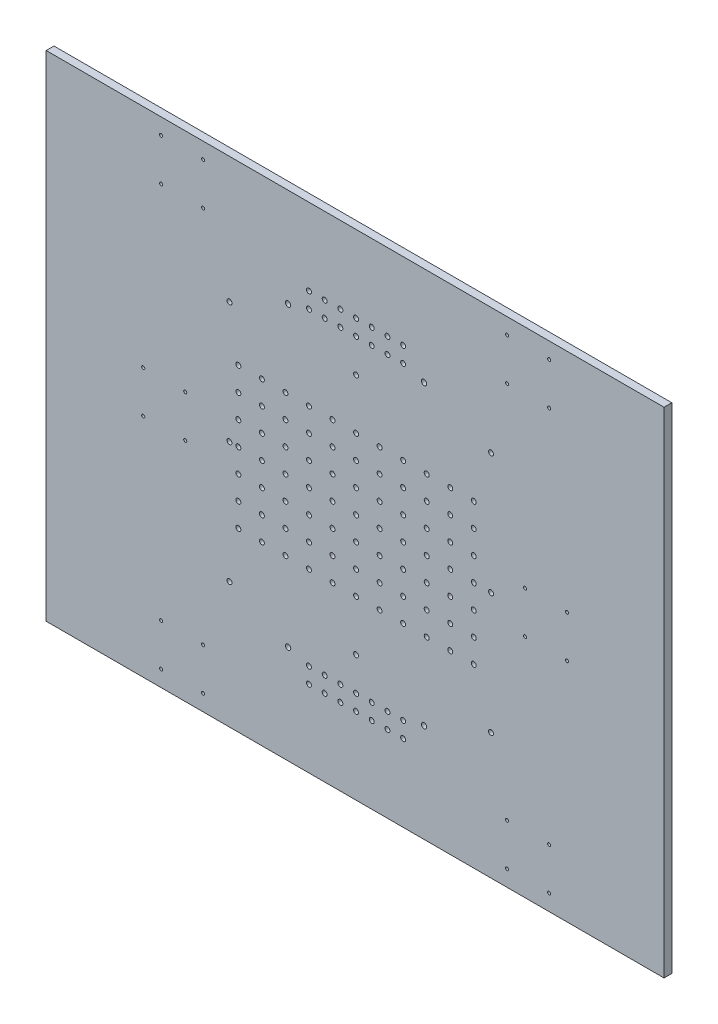
SolidWorks part; units mm, degrees
ref_plane "Front Plane" through (0, 0, 0) normal (0, 0, 1) x (1, 0, 0)
ref_plane "Top Plane" through (0, 0, 0) normal (0, 1, 0) x (1, 0, 0)
ref_plane "Right Plane" through (0, 0, 0) normal (1, 0, 0) x (0, 0, -1)
sketch "Sketch1" plane through (0, 0, 0) normal (0, 0, 1) x (1, 0, 0)
  line L1 (-250, 200) -> (250, 200)
  line L2 (-250, 200) -> (-250, -200)
  line L3 (-250, -200) -> (250, -200)
  line L4 (250, 200) -> (250, -200)
  dimension "D1" = 500
  dimension "D2" = 400
  dimension "D3" = 200
  dimension "D4" = 250
extrude "Base_Plate-Extrude" add sketch "Sketch1" along normal blind 6.3
sketch "Sketch2" plane through (0, 0, 6.3) normal (0, 0, 1) x (1, 0, 0)
  line L0 (140, 239.4193) -> (140, -239.7265) construction
  line L1 (274.5626, 0) -> (-272.804, 0) construction
  line L2 (250, -200) -> (250, 200) construction
  line L3 (274.5626, 170) -> (79.3115, 170) construction
  line L4 (274.5626, -170) -> (79.3115, -170) construction
  line L6 (-154.4486, 296.3867) -> (-154.4486, -298.16) construction
  line L8 (0, 280.9567) -> (0, -269.742) construction
  circle A0 centre (157, 153) radius 1.25
  circle A1 centre (157, 187) radius 1.25
  circle A2 centre (123, 187) radius 1.25
  circle A3 centre (123, 153) radius 1.25
  circle A7 centre (157, -153) radius 1.25
  circle A8 centre (157, -187) radius 1.25
  circle A9 centre (123, -153) radius 1.25
  circle A10 centre (123, -187) radius 1.25
  circle A11 centre (-137.4486, 17) radius 1.25
  circle A12 centre (-137.4486, -17) radius 1.25
  circle A13 centre (-171.4486, -17) radius 1.25
  circle A14 centre (-171.4486, 17) radius 1.25
  circle A15 centre (171.4486, -17) radius 1.25
  circle A16 centre (171.4486, 17) radius 1.25
  circle A17 centre (137.4486, 17) radius 1.25
  circle A18 centre (137.4486, -17) radius 1.25
  circle A19 centre (-157, -153) radius 1.25
  circle A20 centre (-123, -153) radius 1.25
  circle A21 centre (-123, -187) radius 1.25
  circle A22 centre (-157, -187) radius 1.25
  circle A23 centre (-157, 187) radius 1.25
  circle A24 centre (-123, 187) radius 1.25
  circle A25 centre (-123, 153) radius 1.25
  circle A26 centre (-157, 153) radius 1.25
  point P39 (140, -170)
  point P40 (140, 170)
  point P41 (-154.4486, 0)
  point P42 (0, 0)
  point P43 (0, 0)
  point P44 (0, 0)
  point P45 (0, 0)
  point P46 (0, 0)
  point P47 (0, 0)
  point P48 (0, 0)
  dimension "D4" = 2.5
  dimension "D7" = 2.5
  dimension "D8" = 2.5
  dimension "D9" = 2.5
  dimension "D16" = 2.5
  dimension "D17" = 2.5
  dimension "D18" = 2.5
  dimension "D19" = 2.5
  dimension "D29" = 2.5
  dimension "D30" = 2.5
  dimension "D31" = 2.5
  dimension "D32" = 2.5
  dimension "D1" = 110
  dimension "D2" = 170
  dimension "D3" = 170
  dimension "D5" = 17
  dimension "D6" = 17
  dimension "D10" = 17
  dimension "D11" = 17
  dimension "D12" = 17
  dimension "D13" = 17
  dimension "D14" = 17
  dimension "D15" = 17
  dimension "D20" = 17
  dimension "D21" = 17
  dimension "D22" = 17
  dimension "D23" = 17
  dimension "D24" = 17
  dimension "D25" = 17
  dimension "D26" = 17
  dimension "D27" = 17
  dimension "D33" = 17
  dimension "D34" = 17
  dimension "D35" = 17
  dimension "D36" = 17
  dimension "D37" = 17
  dimension "D38" = 17
  dimension "D39" = 17
  dimension "D40" = 17
  dimension "D28" = 340
extrude "Tripod_Adapater_Fasteners-Thru-Hole" cut sketch "Sketch2" against normal through all
sketch "Sketch3" plane through (0, 0, 6.3) normal (0, 0, 1) x (1, 0, 0)
  line L0 (218.6774, 98) -> (-212.5391, 98) construction
  line L1 (218.7113, -98) -> (-212.5283, -98) construction
  line L2 (110, 226.7998) -> (110, -231.3038) construction
  line L3 (250, -200) -> (250, 200) construction
  line L4 (-101.66, 174.4237) -> (-101.66, -178.7911) construction
  line L5 (282.3614, 0) -> (-354.7069, 0) construction
  line L6 (55.78, 225.6084) -> (55.78, -232.4952) construction
  line L7 (-54.22, -232.4952) -> (-54.22, 225.6084) construction
  line L8 (95.7553, 120.25) -> (-187.2723, 120.25) construction
  line L9 (88.1602, -120.25) -> (-163.8184, -120.25) construction
  circle A0 centre (110, 98) radius 2
  circle A1 centre (0.78, 98) radius 2
  circle A2 centre (-101.66, 98) radius 2
  circle A3 centre (-101.66, -98) radius 2
  circle A4 centre (0.78, -98) radius 2
  circle A5 centre (110, -98) radius 2
  circle A8 centre (110, 0) radius 2
  circle A9 centre (-101.66, 0) radius 2
  circle A85 centre (55.78, -120.25) radius 2.15
  circle A86 centre (-54.22, -120.25) radius 2.15
  circle A87 centre (-54.22, 120.25) radius 2.15
  circle A88 centre (55.78, 120.25) radius 2.15
  point P45 (0, 0)
  point P46 (0, 0)
  point P47 (0, 0)
  point P48 (0, 0)
  point P49 (0, 0)
  point P50 (0, 0)
  point P51 (0, 0)
  point P52 (0, 0)
  point P53 (0, 0)
  dimension "D1" = 4
  dimension "D8" = 4
  dimension "D9" = 4
  dimension "D10" = 4
  dimension "D11" = 4
  dimension "D12" = 4
  dimension "D16" = 4
  dimension "D17" = 4
  dimension "D20" = 4.3
  dimension "D21" = 4.3
  dimension "D22" = 4.3
  dimension "D23" = 4.3
  dimension "D3" = 109.22
  dimension "D4" = 102.44
  dimension "D5" = 102.44
  dimension "D6" = 109.22
  dimension "D2" = 196
  dimension "D7" = 98
  dimension "D13" = 140
  dimension "D14" = 98
  dimension "D15" = 98
  dimension "D18" = 110
  dimension "D19" = 240.5
  dimension "D24" = 120.25
  dimension "D25" = 55
extrude "Plate_to_Plate_Mnt-Thru-Hole" cut sketch "Sketch3" against normal through all
sketch "Sketch4" plane through (0, 0, 6.3) normal (0, 0, 1) x (1, 0, 0)
  line L0 (283.705, 0) -> (-313.8392, 0) construction
  circle A0 centre (-94.47, 0) radius 2
  circle A1 centre (-101.66, 0) radius 2 construction
  circle A2 centre (-75.42, 0) radius 2
  circle A3 centre (-56.37, 0) radius 2
  circle A4 centre (-37.32, 0) radius 2
  circle A5 centre (-18.27, 0) radius 2
  circle A6 centre (0.78, 0) radius 2
  circle A7 centre (19.83, 0) radius 2
  circle A8 centre (38.88, 0) radius 2
  circle A9 centre (57.93, 0) radius 2
  circle A10 centre (76.98, 0) radius 2
  circle A11 centre (96.03, 0) radius 2
  circle A12 centre (-94.47, 19.05) radius 2
  circle A13 centre (-75.42, 19.05) radius 2
  circle A14 centre (-56.37, 19.05) radius 2
  circle A15 centre (-37.32, 19.05) radius 2
  circle A16 centre (-18.27, 19.05) radius 2
  circle A17 centre (0.78, 19.05) radius 2
  circle A18 centre (19.83, 19.05) radius 2
  circle A19 centre (38.88, 19.05) radius 2
  circle A20 centre (57.93, 19.05) radius 2
  circle A21 centre (76.98, 19.05) radius 2
  circle A22 centre (96.03, 19.05) radius 2
  circle A23 centre (-94.47, 38.1) radius 2
  circle A24 centre (-75.42, 38.1) radius 2
  circle A25 centre (-56.37, 38.1) radius 2
  circle A26 centre (-37.32, 38.1) radius 2
  circle A27 centre (-18.27, 38.1) radius 2
  circle A28 centre (0.78, 38.1) radius 2
  circle A29 centre (19.83, 38.1) radius 2
  circle A30 centre (38.88, 38.1) radius 2
  circle A31 centre (57.93, 38.1) radius 2
  circle A32 centre (76.98, 38.1) radius 2
  circle A33 centre (96.03, 38.1) radius 2
  circle A34 centre (-94.47, 57.15) radius 2
  circle A35 centre (-75.42, 57.15) radius 2
  circle A36 centre (-56.37, 57.15) radius 2
  circle A37 centre (-37.32, 57.15) radius 2
  circle A38 centre (-18.27, 57.15) radius 2
  circle A39 centre (0.78, 57.15) radius 2
  circle A40 centre (19.83, 57.15) radius 2
  circle A41 centre (38.88, 57.15) radius 2
  circle A42 centre (57.93, 57.15) radius 2
  circle A43 centre (76.98, 57.15) radius 2
  circle A44 centre (96.03, 57.15) radius 2
  circle A45 centre (-94.47, -19.05) radius 2
  circle A46 centre (-75.42, -19.05) radius 2
  circle A47 centre (-56.37, -19.05) radius 2
  circle A48 centre (-37.32, -19.05) radius 2
  circle A49 centre (-18.27, -19.05) radius 2
  circle A50 centre (0.78, -19.05) radius 2
  circle A51 centre (19.83, -19.05) radius 2
  circle A52 centre (38.88, -19.05) radius 2
  circle A53 centre (57.93, -19.05) radius 2
  circle A54 centre (76.98, -19.05) radius 2
  circle A55 centre (96.03, -19.05) radius 2
  circle A56 centre (-94.47, -38.1) radius 2
  circle A57 centre (-75.42, -38.1) radius 2
  circle A58 centre (-56.37, -38.1) radius 2
  circle A59 centre (-37.32, -38.1) radius 2
  circle A60 centre (-18.27, -38.1) radius 2
  circle A61 centre (0.78, -38.1) radius 2
  circle A62 centre (19.83, -38.1) radius 2
  circle A63 centre (38.88, -38.1) radius 2
  circle A64 centre (57.93, -38.1) radius 2
  circle A65 centre (76.98, -38.1) radius 2
  circle A66 centre (96.03, -38.1) radius 2
  circle A67 centre (-94.47, -57.15) radius 2
  circle A68 centre (-75.42, -57.15) radius 2
  circle A69 centre (-56.37, -57.15) radius 2
  circle A70 centre (-37.32, -57.15) radius 2
  circle A71 centre (-18.27, -57.15) radius 2
  circle A72 centre (0.78, -57.15) radius 2
  circle A73 centre (19.83, -57.15) radius 2
  circle A74 centre (38.88, -57.15) radius 2
  circle A75 centre (57.93, -57.15) radius 2
  circle A76 centre (76.98, -57.15) radius 2
  circle A77 centre (96.03, -57.15) radius 2
  dimension "D1" = 7.19
  dimension "D2" = 4
  dimension "D4" = 11
  dimension "D3" = 4
  dimension "D5" = 4
extrude "Center_Perforation-Thru-Hole" cut sketch "Sketch4" against normal through all
sketch "Sketch5" plane through (0, 0, 6.3) normal (0, 0, 1) x (1, 0, 0)
  line L0 (300.3422, 0) -> (-331.6581, 0) construction
  line L1 (0.78, -98) -> (0.78, 98) construction
  circle A0 centre (0.78, -125.08) radius 2
  circle A1 centre (0.78, -98) radius 2 construction
  circle A2 centre (13.48, -125.08) radius 2
  circle A3 centre (26.18, -125.08) radius 2
  circle A4 centre (38.88, -125.08) radius 2
  circle A5 centre (-11.92, -125.08) radius 2
  circle A6 centre (-24.62, -125.08) radius 2
  circle A7 centre (-37.32, -125.08) radius 2
  circle A8 centre (0.78, -137.78) radius 2
  circle A9 centre (13.48, -137.78) radius 2
  circle A10 centre (26.18, -137.78) radius 2
  circle A11 centre (38.88, -137.78) radius 2
  circle A12 centre (-11.92, -137.78) radius 2
  circle A13 centre (-24.62, -137.78) radius 2
  circle A14 centre (-37.32, -137.78) radius 2
  circle A15 centre (-37.32, 137.78) radius 2
  circle A16 centre (-24.62, 137.78) radius 2
  circle A17 centre (-11.92, 137.78) radius 2
  circle A18 centre (38.88, 137.78) radius 2
  circle A19 centre (26.18, 137.78) radius 2
  circle A20 centre (13.48, 137.78) radius 2
  circle A21 centre (0.78, 137.78) radius 2
  circle A22 centre (-37.32, 125.08) radius 2
  circle A23 centre (-24.62, 125.08) radius 2
  circle A24 centre (-11.92, 125.08) radius 2
  circle A25 centre (38.88, 125.08) radius 2
  circle A26 centre (26.18, 125.08) radius 2
  circle A27 centre (13.48, 125.08) radius 2
  circle A28 centre (0.78, 125.08) radius 2
  dimension "D1" = 27.08
  dimension "D2" = 4
  dimension "D3" = 4
  dimension "D5" = 4
  dimension "D4" = 2
extrude "Side-Perforation-Thru-Hole" cut sketch "Sketch5" against normal through all
equation "\"D3@Sketch1\"=\"D2@Sketch1\"/2"
equation "\"D4@Sketch1\"=\"D1@Sketch1\"/2"
equation "\"PLATE_LEN\"=500"
equation "\"D1@Sketch1\"=\"PLATE_LEN\""
equation "\"PLATE_WID\"=400"
equation "\"D2@Sketch1\"=\"PLATE_WID\""
equation "\"PLATE_THICKNESS\"=6.3"
equation "\"D1@Base_Plate-Extrude\" = \"PLATE_THICKNESS\""
equation "\"FRONT_TO_TRIPOD\"=110"
equation "\"D1@Sketch2\"=\"FRONT_TO_TRIPOD\""
equation "\"TRIPOD_STRIDE\"=340"
equation "\"D2@Sketch2\"=\"TRIPOD_STRIDE\"/2"
equation "\"D3@Sketch2\"=\"TRIPOD_STRIDE\"/2"
equation "\"D28@Sketch2\"=\"TRIPOD_STRIDE\""
equation "\"D7@Sketch3\"=\"D2@Sketch3\"/2"
equation "\"D14@Sketch3\"=\"D2@Sketch3\"/2"
equation "\"D15@Sketch3\"=\"D2@Sketch3\"/2"
equation "\"D24@Sketch3\"=\"D19@Sketch3\"/2"
equation "\"D25@Sketch3\"=\"D18@Sketch3\"/2"
